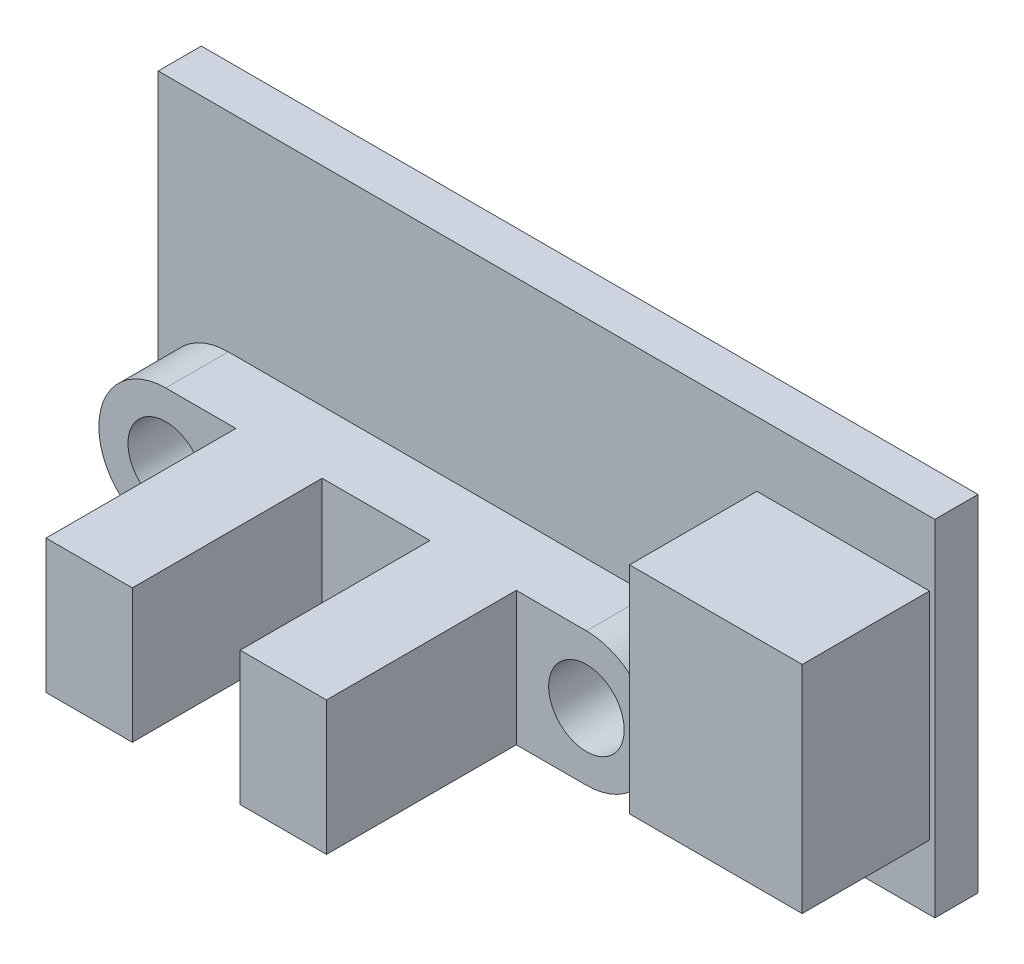
SolidWorks part; units mm, degrees
ref_plane "Спереди" through (0, 0, 0) normal (0, 0, 1) x (1, 0, 0)
ref_plane "Сверху" through (0, 0, 0) normal (0, 1, 0) x (1, 0, 0)
ref_plane "Справа" through (0, 0, 0) normal (1, 0, 0) x (0, 0, -1)
sketch "Эскиз1" plane through (0, 0, 0) normal (0, 0, 1) x (1, 0, 0)
  line L1 (0, 0) -> (36, 0)
  line L2 (0, 0) -> (0, -16)
  line L3 (0, -16) -> (36, -16)
  line L4 (36, 0) -> (36, -16)
  dimension "D1" = 16
  dimension "D2" = 36
extrude "Бобышка-Вытянуть1" add sketch "Эскиз1" along normal blind 2
sketch "Эскиз2" plane through (0, 0, 2) normal (0, 0, 1) x (1, 0, 0)
  line L0 (0, -16) -> (36, -16) construction
  line L1 (0, 0) -> (0, -16) construction
  line L2 (3.25, -9.65) -> (22.75, -9.65)
  line L3 (22.75, -15.85) -> (3.25, -15.85)
  arc A0 (3.25, -9.65) -> (3.25, -15.85) centre (3.25, -12.75) ccw
  arc A1 (22.75, -15.85) -> (22.75, -9.65) centre (22.75, -12.75) ccw
  dimension "D1" = 6.2
  dimension "D2" = 6.2
  dimension "D3" = 19.5
  dimension "D4" = 3.25
  dimension "D5" = 3.25
extrude "Бобышка-Вытянуть2" add sketch "Эскиз2" along normal blind 2.9
sketch "Эскиз3" plane through (0, 0, 4.9) normal (0, 0, 1) x (1, 0, 0)
  line L1 (6.5, -9.65) -> (10.5, -9.65)
  line L2 (6.5, -9.65) -> (6.5, -15.85)
  line L3 (6.5, -15.85) -> (10.5, -15.85)
  line L4 (10.5, -9.65) -> (10.5, -15.85)
  line L6 (22.75, -9.65) -> (3.25, -9.65) construction
  line L7 (3.25, -15.85) -> (22.75, -15.85) construction
  line L9 (15.5, -9.65) -> (19.5, -9.65)
  line L10 (15.5, -9.65) -> (15.5, -15.85)
  line L11 (15.5, -15.85) -> (19.5, -15.85)
  line L12 (19.5, -9.65) -> (19.5, -15.85)
  arc A0 (3.25, -9.65) -> (3.25, -15.85) centre (3.25, -12.75) ccw construction
  arc A1 (22.75, -15.85) -> (22.75, -9.65) centre (22.75, -12.75) ccw construction
  dimension "D7" = 3.25
  dimension "D1" = 6.2
  dimension "D2" = 4
  dimension "D3" = 6.2
  dimension "D4" = 4
  dimension "D5" = 5
  dimension "D6" = 3.25
extrude "Бобышка-Вытянуть3" add sketch "Эскиз3" along normal blind 8.8
sketch "Эскиз4" plane through (0, 0, 2) normal (0, 0, 1) x (1, 0, 0)
  line L0 (36, -16) -> (36, 0) construction
  line L1 (35.75, -3) -> (27.75, -3)
  line L2 (35.75, -3) -> (35.75, -13)
  line L3 (35.75, -13) -> (27.75, -13)
  line L4 (27.75, -3) -> (27.75, -13)
  point P6 (36, -8)
  point P7 (35.75, -8)
  dimension "D1" = 10
  dimension "D2" = 8
  dimension "D3" = 0.25
extrude "Бобышка-Вытянуть4" add sketch "Эскиз4" along normal blind 5.9
sketch "Эскиз5" plane through (0, 0, 4.9) normal (0, 0, 1) x (1, 0, 0)
  circle A0 centre (3.25, -12.75) radius 1.75
  circle A1 centre (22.75, -12.75) radius 1.75
  dimension "D1" = 3.5
  dimension "D2" = 3.5
extrude "Вырез-Вытянуть1" cut sketch "Эскиз5" against normal through all
